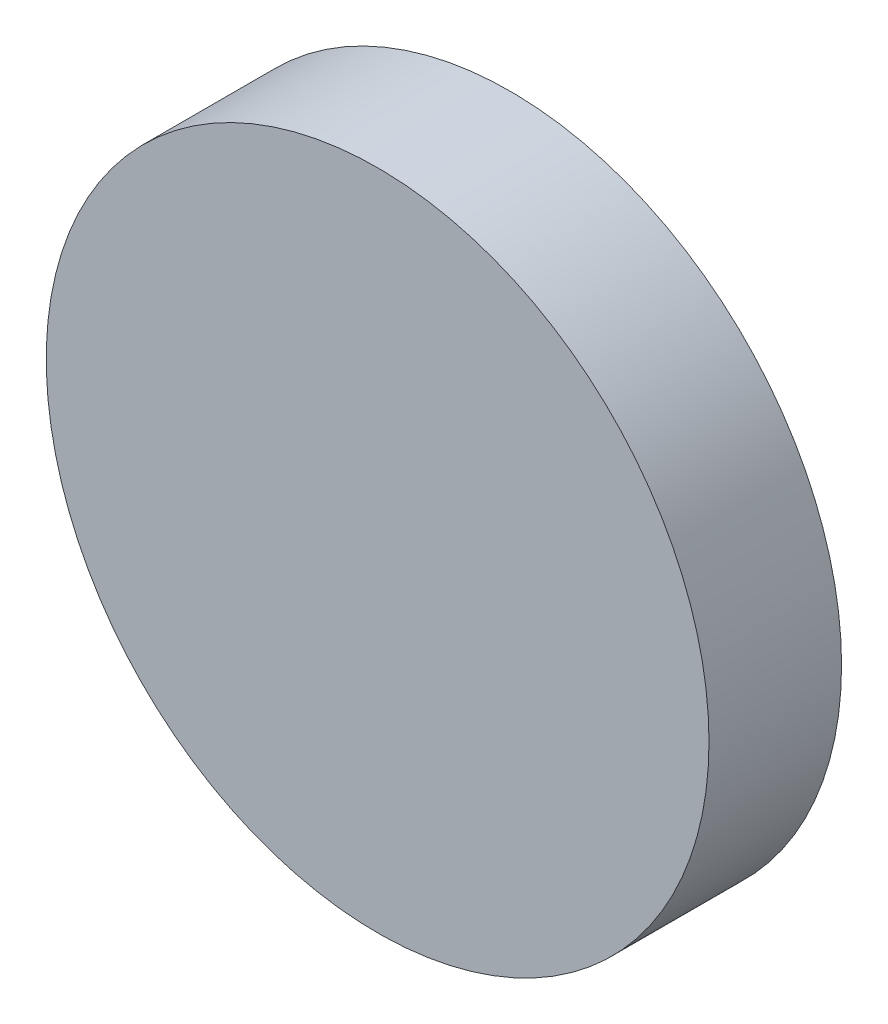
SolidWorks part; units mm, degrees
ref_plane "前视基准面" through (0, 0, 0) normal (0, 0, 1) x (1, 0, 0)
ref_plane "上视基准面" through (0, 0, 0) normal (0, 1, 0) x (1, 0, 0)
ref_plane "右视基准面" through (0, 0, 0) normal (1, 0, 0) x (0, 0, -1)
sketch "草图1" plane through (0, 0, 0) normal (0, 0, 1) x (1, 0, 0)
  circle A0 centre (0, 0) radius 12.5
  dimension "D1" = 25
extrude "凸台-拉伸1" add sketch "草图1" along normal blind 5
